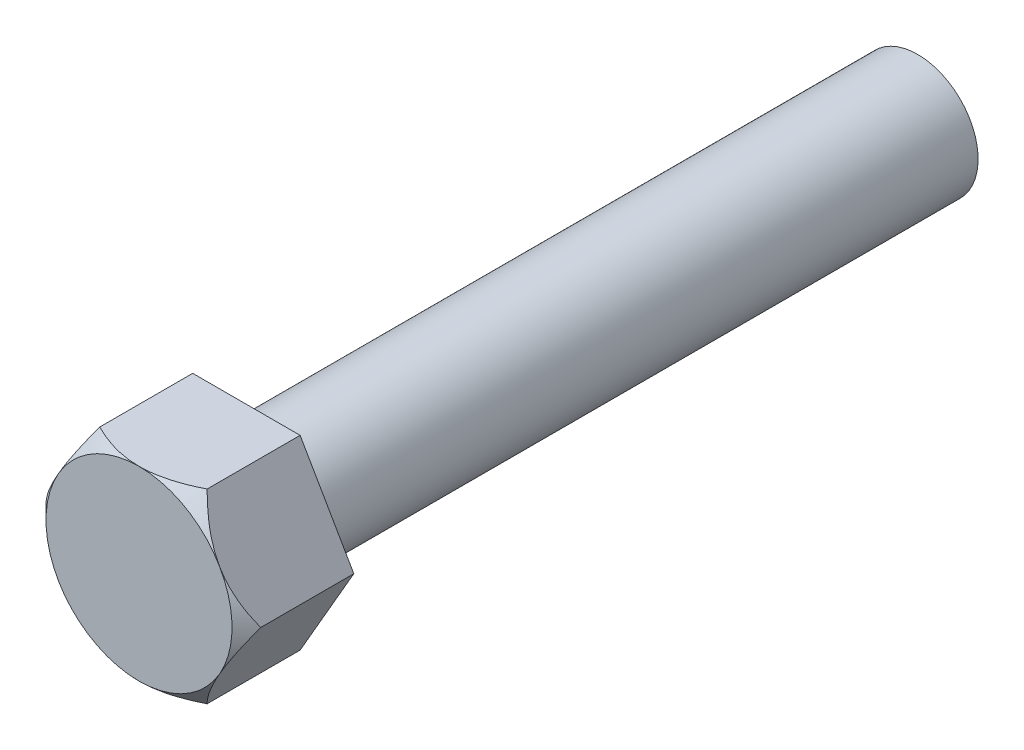
SolidWorks part; units mm, degrees
ref_plane "Front Plane" through (0, 0, 0) normal (0, 0, 1) x (1, 0, 0)
ref_plane "Top Plane" through (0, 0, 0) normal (0, 1, 0) x (1, 0, 0)
ref_plane "Right Plane" through (0, 0, 0) normal (1, 0, 0) x (0, 0, -1)
sketch "Sketch1" plane through (0, 0, 0) normal (0, 0, 1) x (1, 0, 0)
  line L1 (-2, 3.4641) -> (-4, 0)
  line L2 (-4, 0) -> (-2, -3.4641)
  line L3 (-2, -3.4641) -> (2, -3.4641)
  line L4 (2, -3.4641) -> (4, 0)
  line L5 (4, 0) -> (2, 3.4641)
  line L6 (2, 3.4641) -> (-2, 3.4641)
  circle A0 centre (0, 0) radius 3.4641 construction
  dimension "D1" = 8
extrude "Boss-Extrude1" add sketch "Sketch1" along normal blind 4
sketch "Sketch2" plane through (0, 0, 4) normal (0, 0, 1) x (1, 0, 0)
  circle A0 centre (0, 0) radius 3.4641
extrude "Cut-Extrude1" cut sketch "Sketch2" against normal blind 4 draft 45 flip side to cut
sketch "Sketch3" plane through (0, 0, 0) normal (0, 0, -1) x (-1, 0, 0)
  circle A0 centre (0, 0) radius 2.25
  dimension "D1" = 4.5
extrude "Boss-Extrude2" add sketch "Sketch3" along normal blind 25
